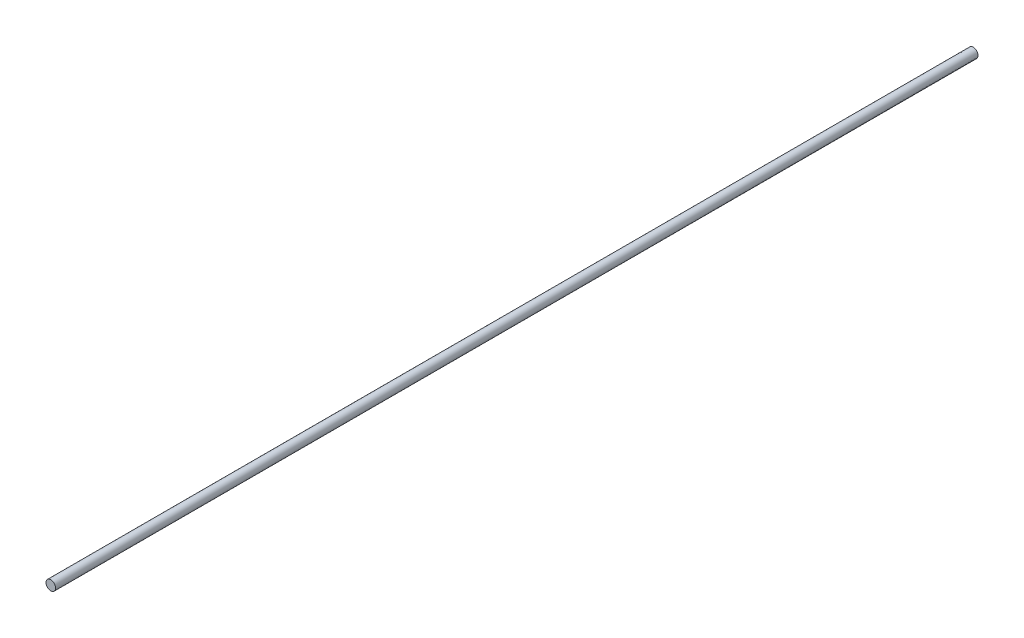
SolidWorks part; units mm, degrees
ref_plane "Front Plane" through (0, 0, 0) normal (0, 0, 1) x (1, 0, 0)
ref_plane "Top Plane" through (0, 0, 0) normal (0, 1, 0) x (1, 0, 0)
ref_plane "Right Plane" through (0, 0, 0) normal (1, 0, 0) x (0, 0, -1)
sketch "Sketch1" plane through (0, 0, 0) normal (0, 0, 1) x (1, 0, 0)
  circle A0 centre (0, 0) radius 6.35
  dimension "D1" = 12.7
extrude "Boss-Extrude1" add sketch "Sketch1" along normal blind 1219.2
ref_plane "Plane1" through (0, 0, 609.6) normal (0, 0, 1) x (1, 0, 0)
